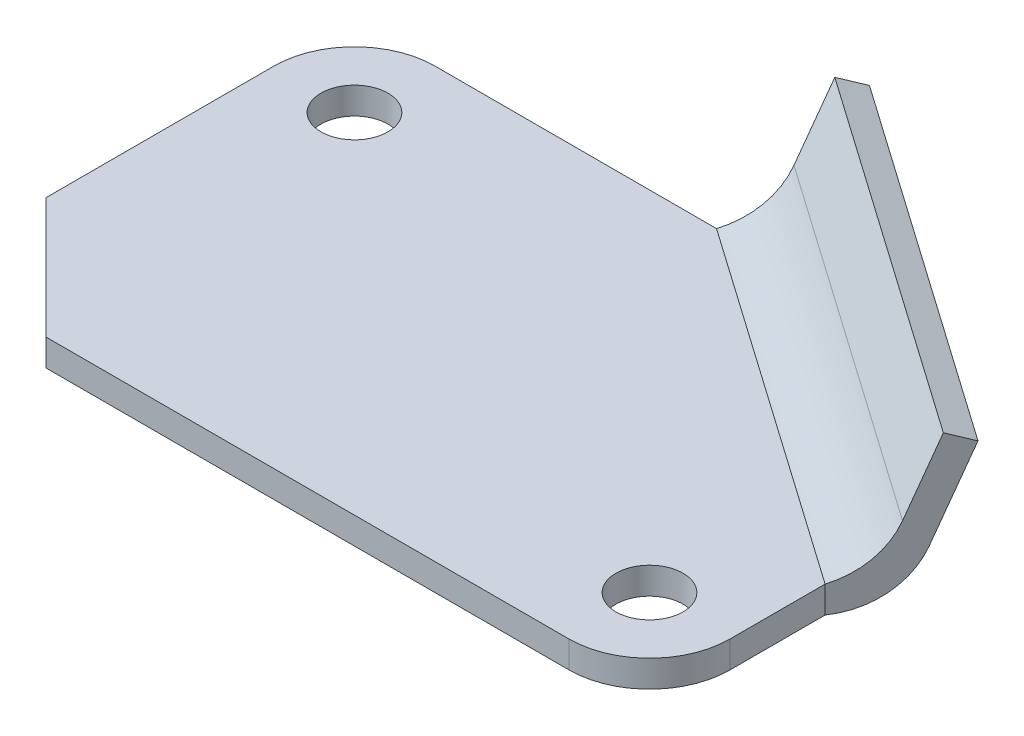
SolidWorks part; units mm, degrees
material "Manganese Bronze"
ref_plane "Front Plane" through (0, 0, 0) normal (0, 0, 1) x (1, 0, 0)
ref_plane "Top Plane" through (0, 0, 0) normal (0, 1, 0) x (1, 0, 0)
ref_plane "Right Plane" through (0, 0, 0) normal (1, 0, 0) x (0, 0, -1)
sketch "Sketch2" plane through (0, 0, 0) normal (0, 1, 0) x (1, 0, 0)
  line L0 (0, 32) -> (-42, 32)
  line L1 (-54, -32) -> (54, -32) construction
  line L2 (-54, -32) -> (-54, 32) construction
  line L3 (-54, 32) -> (54, 32) construction
  line L4 (54, -32) -> (54, 32) construction
  line L5 (-54, -32) -> (54, 32) construction
  line L6 (-54, 32) -> (54, -32) construction
  line L7 (-54, 20) -> (-54, -14)
  line L8 (-36, -32) -> (42, -32)
  line L9 (54, -20) -> (54, -5.8112)
  line L10 (54, -5.8112) -> (0, 32)
  line L11 (-54, -14) -> (-36, -32)
  circle A0 centre (-42, 20) radius 5
  circle A1 centre (42, -20) radius 5
  arc A2 (42, -32) -> (54, -20) centre (42, -20) ccw
  arc A3 (-42, 32) -> (-54, 20) centre (-42, 20) ccw
  point P0 (0, 0)
  dimension "D3" = 10
  dimension "D2" = 12
  dimension "D1" = 64
  dimension "D4" = 108
  dimension "D5" = 54
  dimension "D6" = 35
extrude "Boss-Extrude1" add sketch "Sketch2" along normal blind 4
ref_plane "Plane1" through (38.9649, 0, 27.2835) normal (0.8192, 0, 0.5736) x (0, -1, 0)
sketch "Sketch3" plane through (38.9649, 0, 27.2835) normal (0.8192, 0, 0.5736) x (0, -1, 0)
  line L1 (-11.165, 34.5038) -> (-21.9837, 38.8748)
  line L2 (-21.9837, 38.8748) -> (-20.4853, 42.5836)
  line L3 (-20.4853, 42.5836) -> (-7.5047, 37.3391)
  line L5 (-4, 26.2129) -> (0, 26.2129)
  line L6 (-4, 14.5901) -> (-4, 26.2129) construction
  line L7 (0, 14.5901) -> (0, 26.2129) construction
  arc A0 (-7.5047, 37.3391) -> (0, 26.2129) centre (-12, 26.2129) cw
  arc A1 (-4, 26.2129) -> (-11.165, 34.5038) centre (-15.6602, 23.3776) ccw
  point P2 (-29.4172, 55.4931)
  point P7 (-24.4946, 55.2624)
  point P11 (-5.8041, 40.1869)
  point P14 (-37.8779, 54.1087)
  point P15 (0, 0)
  point P16 (0, 0)
  point P18 (-7.3955, 38.9542)
  point P21 (-11.165, 34.5038)
  dimension "D3" = 12
  dimension "D1" = 112
  dimension "D2" = 4
  dimension "D4" = 14
extrude "Boss-Extrude2" add sketch "Sketch3" against normal up to vertex (65.9218 mm away) separate body
